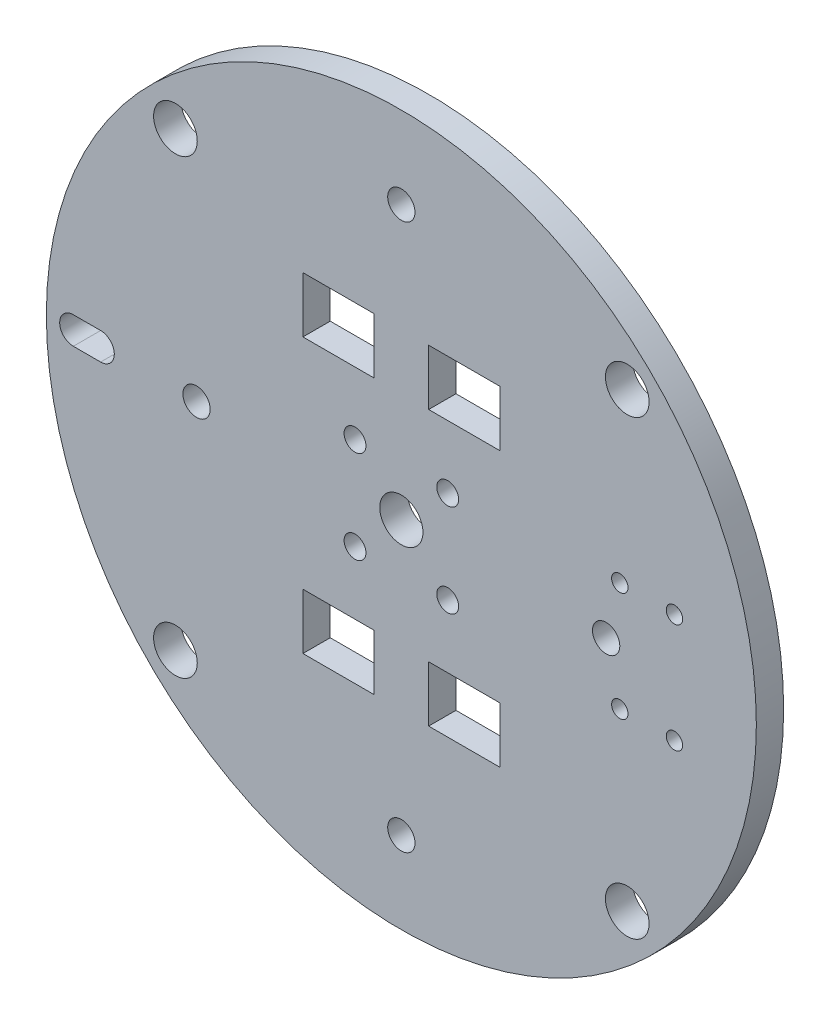
SolidWorks part; units mm, degrees
ref_plane "Front Plane" through (0, 0, 0) normal (0, 0, 1) x (1, 0, 0)
ref_plane "Top Plane" through (0, 0, 0) normal (0, 1, 0) x (1, 0, 0)
ref_plane "Right Plane" through (0, 0, 0) normal (1, 0, 0) x (0, 0, -1)
sketch "Sketch1" plane through (0, 0, 0) normal (0, 0, 1) x (1, 0, 0)
  line L2 (5, -20) -> (18.02, -20)
  line L3 (18.02, -20) -> (18.02, -30.2)
  line L4 (18.02, -30.2) -> (5, -30.2)
  line L6 (5, -20) -> (5, -30.2)
  line L7 (-5, -20) -> (-18.02, -20)
  line L8 (-18.02, -20) -> (-18.02, -30.2)
  line L9 (-18.02, -30.2) -> (-5, -30.2)
  line L10 (-5, -30.2) -> (-5, -20)
  line L19 (-5, 20) -> (-18.02, 20)
  line L20 (-18.02, 20) -> (-18.02, 30.2)
  line L21 (-18.02, 30.2) -> (-5, 30.2)
  line L22 (-5, 30.2) -> (-5, 20)
  line L24 (5, 20) -> (5, 30.2)
  line L25 (5, 30.2) -> (18.02, 30.2)
  line L26 (18.02, 30.2) -> (18.02, 20)
  line L27 (18.02, 20) -> (5, 20)
  line L32 (-55.0566, 0) -> (-60.0566, 0) construction
  line L35 (-55.0566, -2.5) -> (-60.0566, -2.5)
  line L36 (-55.0566, 2.5) -> (-60.0566, 2.5)
  circle A0 centre (0, 0) radius 65
  circle A1 centre (-37.5, 0) radius 2.5
  circle A2 centre (37.5, 0) radius 2.5
  circle A3 centre (0, 50) radius 2.5
  circle A4 centre (0, -50) radius 2.5
  circle A6 centre (0, 0) radius 3.95
  circle A7 centre (50, 10) radius 1.5
  circle A8 centre (50, -10) radius 1.5
  circle A9 centre (40, 10) radius 1.5
  circle A10 centre (40, -10) radius 1.5
  circle A12 centre (-41.3657, 41.3657) radius 4
  circle A13 centre (41.3657, -41.3657) radius 4
  circle A14 centre (41.3657, 41.3657) radius 4
  circle A15 centre (-41.3657, -41.3657) radius 4
  circle A17 centre (8.4853, 8.4853) radius 2
  circle A18 centre (8.4853, -8.4853) radius 2
  circle A19 centre (-8.4853, -8.4853) radius 2
  circle A20 centre (-8.4853, 8.4853) radius 2
  arc A25 (-55.0566, -2.5) -> (-55.0566, 2.5) centre (-55.0566, 0) ccw
  arc A26 (-60.0566, 2.5) -> (-60.0566, -2.5) centre (-60.0566, 0) ccw
  point P6 (0, 0)
  point P11 (0, 0)
  point P26 (0, 0)
  point P37 (0, 0)
  point P44 (-57.5566, 0)
extrude "Boss-Extrude1" add sketch "Sketch1" along normal blind 5
